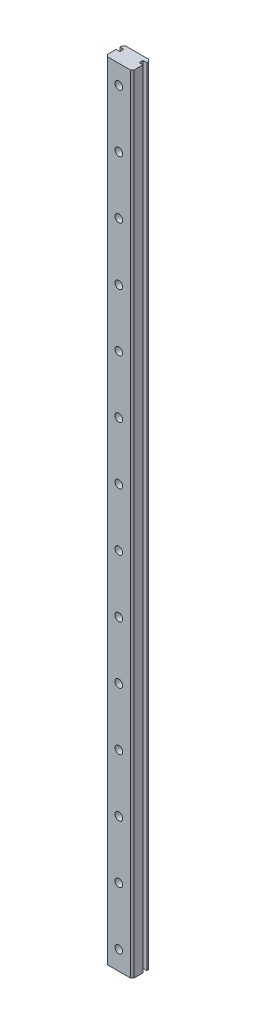
SolidWorks part; units mm, degrees
material "AISI 304"
ref_plane "前视基准面" through (0, 0, 0) normal (0, 0, 1) x (1, 0, 0)
ref_plane "上视基准面" through (0, 0, 0) normal (0, 1, 0) x (1, 0, 0)
ref_plane "右视基准面" through (0, 0, 0) normal (1, 0, 0) x (0, 0, -1)
other "Configuration Table"
sketch "草图1" plane through (0, 0, 0) normal (0, 1, 0) x (1, 0, 0)
  line L0 (0, 0) -> (0, 7.157) construction
  line L1 (-3.5, -2.4) -> (3.5, -2.4)
  line L2 (-3.5, -2.4) -> (-3.5, 2.4)
  line L3 (-3.5, 2.4) -> (3.5, 2.4)
  line L4 (3.5, -2.4) -> (3.5, 2.4)
  line L5 (-3.5, -2.4) -> (3.5, 2.4) construction
  line L6 (-3.5, 2.4) -> (3.5, -2.4) construction
  line L7 (3.5, 1.4) -> (2.5, 1.4)
  line L8 (2.5, 1.4) -> (2.5, 0.4)
  line L9 (2.5, 0.4) -> (3.5, 0.4)
  line L10 (-2.5, 0.4) -> (-3.5, 0.4)
  line L11 (-2.5, 1.4) -> (-2.5, 0.4)
  line L12 (-3.5, 1.4) -> (-2.5, 1.4)
  point P0 (0, 0)
  dimension "D1" = 7
  dimension "D2" = 4.8
  dimension "D3" = 1
  dimension "D4" = 1
  dimension "D5" = 1
extrude "凸台-拉伸1" add sketch "草图1" along normal blind 205 contours L2 L12 L11 L10 L1 L4 L9 L8 L7 L3
sketch "草图2" plane through (0, 0, -2.4) normal (0, 0, -1) x (-1, 0, 0)
  line L0 (3.5, 0) -> (-3.5, 0) construction
  line L1 (-3.5, 205) -> (-3.5, 0) construction
  circle A0 centre (0, 5) radius 1
  circle A1 centre (0, 20) radius 1
  circle A2 centre (0, 35) radius 1
  circle A3 centre (0, 50) radius 1
  circle A4 centre (0, 65) radius 1
  circle A5 centre (0, 80) radius 1
  circle A6 centre (0, 95) radius 1
  circle A7 centre (0, 110) radius 1
  circle A8 centre (0, 125) radius 1
  circle A9 centre (0, 140) radius 1
  circle A10 centre (0, 155) radius 1
  circle A11 centre (0, 170) radius 1
  circle A12 centre (0, 185) radius 1
  circle A13 centre (0, 200) radius 1
  dimension "D1" = 2
  dimension "D2" = 5
  dimension "D5" = 15
  dimension "D3" = 3.5
  dimension "D4" = 14
extrude "切除-拉伸1" cut sketch "草图2" against normal blind 10
chamfer "倒角1" distance 0.5 angle 45 4 edges at (-3.5, 102.5, 2.4) (3.5, 102.5, 2.4) (-3.5, 102.5, -2.4) (3.5, 102.5, -2.4)
sketch "草图3" plane through (0, 0, -2.4) normal (0, 0, -1) x (-1, 0, 0)
  circle A0 centre (0, 5) radius 2.3833
  circle A1 centre (0, 20) radius 2.3833
  circle A2 centre (0, 35) radius 2.3833
  circle A3 centre (0, 50) radius 2.3833
  circle A4 centre (0, 65) radius 2.3833
  circle A5 centre (0, 80) radius 2.3833
  circle A6 centre (0, 95) radius 2.3833
  circle A7 centre (0, 110) radius 2.3833
  circle A8 centre (0, 125) radius 2.3833
  circle A9 centre (0, 140) radius 2.3833
  circle A10 centre (0, 155) radius 2.3833
  circle A11 centre (0, 170) radius 2.3833
  circle A12 centre (0, 185) radius 2.3833
  circle A13 centre (0, 200) radius 2.3833
  dimension "D1" = 4.7666
  dimension "D3" = 15
  dimension "D2" = 14
extrude "切除-拉伸2" cut sketch "草图3" against normal blind 1
